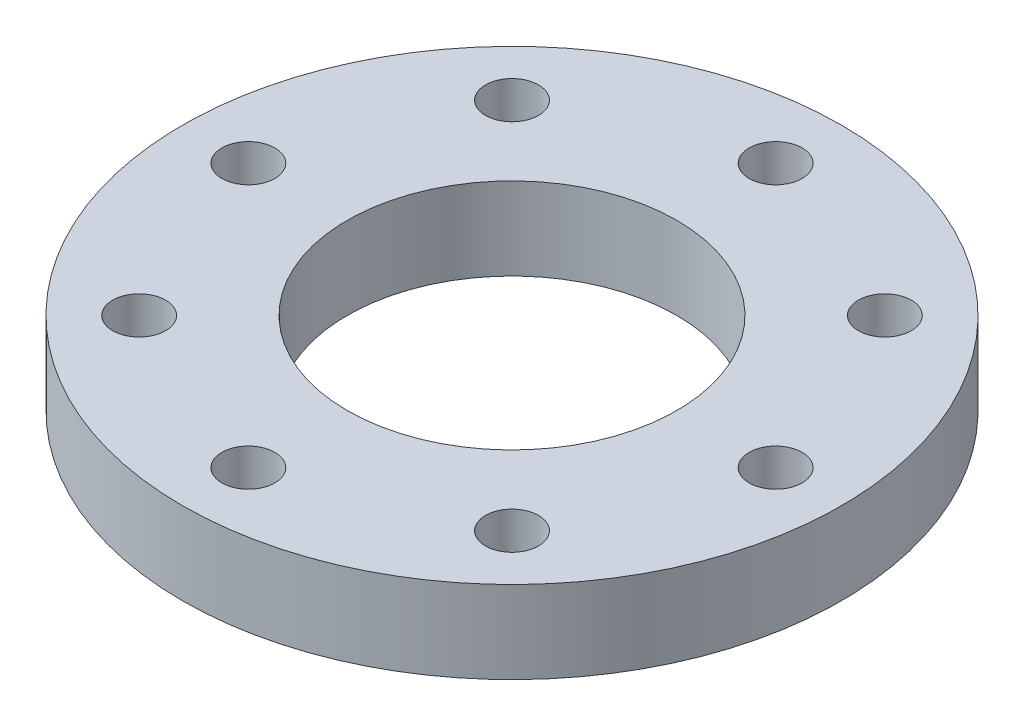
SolidWorks part; units mm, degrees
material "PET"
ref_plane "Front" through (0, 0, 0) normal (0, 0, 1) x (1, 0, 0)
ref_plane "Top" through (0, 0, 0) normal (0, 1, 0) x (1, 0, 0)
ref_plane "Right" through (0, 0, 0) normal (1, 0, 0) x (0, 0, -1)
sketch "Sketch1" plane through (0, 0, 0) normal (0, 1, 0) x (1, 0, 0)
  circle A0 centre (0, 0) radius 31.75
  circle A1 centre (0, 0) radius 15.875
  dimension "D1" = 63.5
  dimension "D2" = 31.75
extrude "Boss-Extrude1" add sketch "Sketch1" along normal blind 7.9375
hole_wizard "#10 Clearance Hole1" positions "Sketch2" profile "Sketch3" hole size "#10" standard "ANSI Inch" end condition through all
sketch "Sketch2" plane through (0, 7.9375, 0) normal (0, 1, 0) x (1, 0, 0)
  circle A0 centre (0, 0) radius 25.4 construction
  point P0 (0, 25.4)
  point P11 (17.9605, 17.9605)
  point P12 (25.4, 0)
  point P13 (17.9605, -17.9605)
  point P14 (0, -25.4)
  point P15 (-17.9605, -17.9605)
  point P16 (-25.4, 0)
  point P17 (-17.9605, 17.9605)
  point P19 (19.1846, 16.6467)
  point P20 (25.3851, -0.8688)
  dimension "D1" = 50.8
  dimension "D2" = 8
sketch "Sketch3" plane through (0, 7.9375, -25.4) normal (1, 0, 0) x (0, 0, 1)
  line L0 (0, 0) -> (0, 7.9375)
  line L1 (0, 7.9375) -> (2.5527, 7.9375)
  line L2 (2.5527, 7.9375) -> (2.5527, 0)
  line L5 (2.5527, 0) -> (0, 0)
  line L11 (0, -6.35) -> (0, 107.95) construction
  dimension "Thru Hole Dia." = 5.1054
  dimension "Thru Hole Depth" = 7.9375
